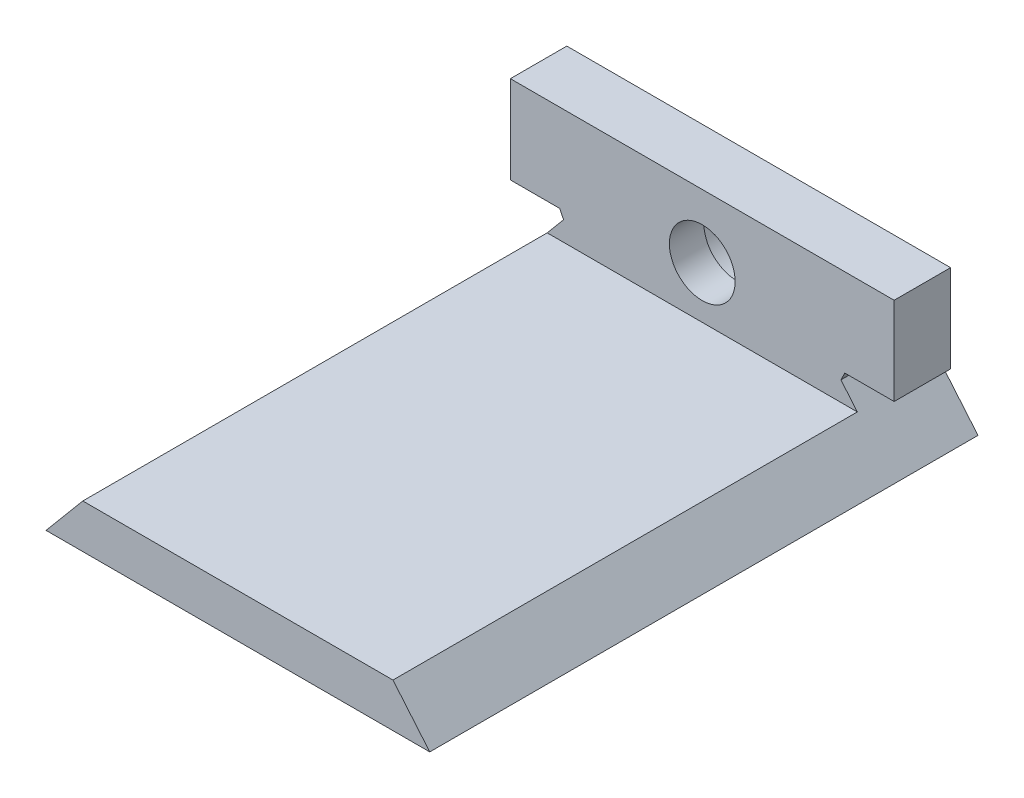
SolidWorks part; units mm, degrees
material "Сталь AISI 1020, холоднокатаная"
ref_plane "Спереди" through (0, 0, 0) normal (0, 0, 1) x (1, 0, 0)
ref_plane "Сверху" through (0, 0, 0) normal (0, 1, 0) x (1, 0, 0)
ref_plane "Справа" through (0, 0, 0) normal (1, 0, 0) x (0, 0, -1)
sketch "Эскиз1" plane through (0, 0, 0) normal (1, 0, 0) x (0, 0, -1)
  line L0 (-20.9863, 0) -> (79.0137, 0)
  line L1 (79.0137, 0) -> (79.0137, 32)
  line L2 (74.0137, 37) -> (71.9226, 37)
  line L3 (49.0137, 8) -> (-20.9863, 8)
  line L4 (-20.9863, 8) -> (-20.9863, 0)
  line L5 (67.8268, 34.8679) -> (49.0137, 8)
  arc A0 (71.9226, 37) -> (67.8268, 34.8679) centre (71.9226, 32) ccw
  arc A1 (79.0137, 32) -> (74.0137, 37) centre (74.0137, 32) ccw
  point P11 (79.0137, 37)
  dimension "D4" = 5
  dimension "D1" = 35
  dimension "D2" = 37
  dimension "D3" = 8
  dimension "D6" = 100
extrude "Бобышка-Вытянуть1" add sketch "Эскиз1" along normal blind 70
sketch "Эскиз2" plane through (0, 0, -79.0137) normal (0, 0, -1) x (-1, 0, 0)
  line L0 (-61, 13) -> (-70, 13)
  line L1 (-60.2938, 11.5675) -> (-70, 0)
  line L2 (-70, 0) -> (-70, 32) construction
  line L3 (-70, 13) -> (-70, 0)
  line L4 (-61, 13) -> (-60.2938, 11.5675)
  line L5 (-35, 0) -> (-35, 37) construction
  line L6 (-70, 0) -> (0, 0) construction
  line L7 (-70, 37) -> (0, 37) construction
  line L8 (-9, 13) -> (-9.7062, 11.5675)
  line L9 (0, 13) -> (0, 0)
  line L10 (-9.7062, 11.5675) -> (0, 0)
  line L11 (-9, 13) -> (0, 13)
  point P0 (-61, 13)
  dimension "D1" = 13
  dimension "D2" = 50
  dimension "D3" = 9
extrude "Вырез-Вытянуть1" cut sketch "Эскиз2" against normal blind 163
sketch "Эскиз3" plane through (0, 0, 0) normal (-1, 0, 0) x (0, 0, 1)
  line L0 (-79.0137, 10) -> (-74.0137, 10)
  line L1 (-79.0137, 13) -> (-79.0137, 32) construction
  line L2 (-74.0137, 10) -> (-74.0137, 38.9842)
  line L3 (-79.0137, 10) -> (-79.0137, 38.9842)
  line L5 (-79.0137, 38.9842) -> (-74.0137, 38.9842)
  line L7 (20.9863, 0) -> (-79.0137, 0) construction
  dimension "D1" = 5
  dimension "D2" = 10
extrude "Вырез-Вытянуть2" cut sketch "Эскиз3" against normal blind 74.1987
sketch "Эскиз4" plane through (0, 0, 0) normal (-1, 0, 0) x (0, 0, 1)
  line L0 (20.9863, 0) -> (-79.0137, 0) construction
  line L1 (-75.2485, 39.193) -> (-54.9891, 39.193)
  line L2 (-75.2485, 39.193) -> (-75.2485, 29)
  line L3 (-75.2485, 29) -> (-54.9891, 29)
  line L4 (-54.9891, 39.193) -> (-54.9891, 29)
  dimension "D1" = 29
extrude "Вырез-Вытянуть3" cut sketch "Эскиз4" against normal blind 77.1987
sketch "Эскиз5" plane through (70, 0, 0) normal (1, 0, 0) x (0, 0, -1)
  line L0 (-20.9863, 8) -> (49.0137, 8) construction
  line L1 (63.7181, 29) -> (41.1394, 29)
  line L2 (63.7181, 29) -> (63.7181, 8)
  line L3 (63.7181, 8) -> (41.1394, 8)
  line L4 (41.1394, 29) -> (41.1394, 8)
extrude "Вырез-Вытянуть4" cut sketch "Эскиз5" against normal blind 77
sketch "Эскиз7" plane through (0, 0, -74.0137) normal (0, 0, -1) x (-1, 0, 0)
  line L0 (-35, 29) -> (-35, 8) construction
  line L1 (0, 29) -> (-70, 29) construction
  line L2 (-6.7128, 8) -> (-63.2872, 8) construction
  circle A0 centre (-35, 17.4361) radius 6
  dimension "D1" = 12
extrude "Вырез-Вытянуть5" cut sketch "Эскиз7" against normal blind 37
sketch "Эскиз8" plane through (0, 0, -74.0137) normal (0, 0, -1) x (-1, 0, 0)
  circle A0 centre (-35, 17.4361) radius 8
  dimension "D1" = 16
extrude "Вырез-Вытянуть6" cut sketch "Эскиз8" against normal blind 4
